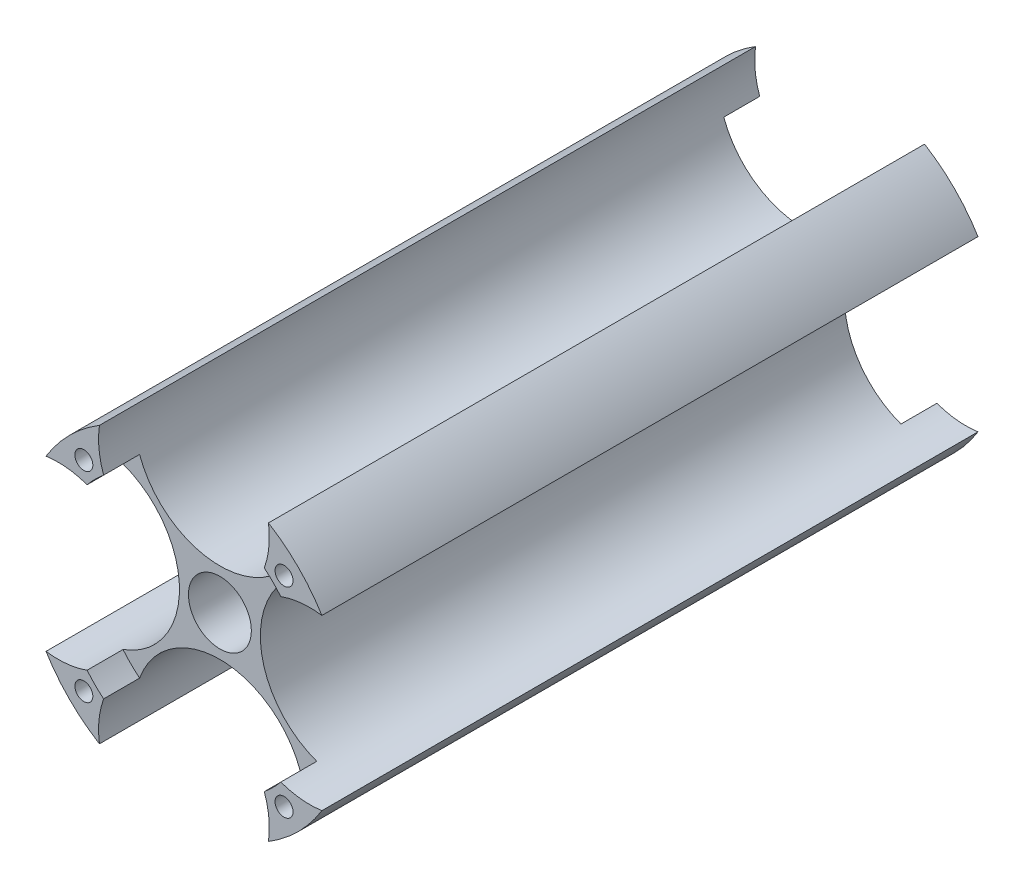
SolidWorks part; units mm, degrees
material "ABS"
ref_plane "Спереди" through (0, 0, 0) normal (0, 0, 1) x (1, 0, 0)
ref_plane "Сверху" through (0, 0, 0) normal (0, 1, 0) x (1, 0, 0)
ref_plane "Справа" through (0, 0, 0) normal (1, 0, 0) x (0, 0, -1)
sketch "Эскиз1" plane through (0, 0, 0) normal (0, 0, 1) x (1, 0, 0)
  line L0 (0, 0) -> (0, -18) construction
  line L1 (0, 0) -> (0, 18) construction
  line L2 (0, 0) -> (-18.5984, 18.5984) construction
  line L3 (0, 0) -> (-14, 0) construction
  circle A0 centre (0, 0) radius 18
  circle A1 centre (0, -14) radius 9.5
  circle A2 centre (-14, 0) radius 9.5
  circle A3 centre (0, 14) radius 9.5
  circle A7 centre (0, 0) radius 3.5
  circle A8 centre (14, 0) radius 9.5
  circle A9 centre (-11.1369, 11.1369) radius 1
  circle A10 centre (11.1369, 11.1369) radius 1
  circle A11 centre (11.1369, -11.1369) radius 1
  circle A12 centre (-11.1369, -11.1369) radius 1
  point P13 (0, 0)
  point P17 (11.5447, 10.6852)
  point P18 (0, 0)
  point P20 (0, 0)
  point P28 (0, 0)
  dimension "D1" = 19
  dimension "D4" = 36
  dimension "D5" = 45
  dimension "D7" = 7
  dimension "D6" = 2
  dimension "D2" = 14
  dimension "D8" = 15.75
  dimension "D3" = 4
  dimension "D9" = 4
extrude "Бобышка-Вытянуть1" add sketch "Эскиз1" along normal blind 65
sketch "Эскиз2" plane through (0, 0, 65) normal (0, 0, 1) x (1, 0, 0)
  circle A0 centre (0, 0) radius 14
  circle A1 centre (14, 0) radius 9.5
  circle A2 centre (14, 0) radius 9.5
  circle A3 centre (0, 14) radius 9.5
  circle A4 centre (0, 14) radius 9.5
  circle A5 centre (-14, 0) radius 9.5
  circle A6 centre (-14, 0) radius 9.5
  circle A7 centre (0, -14) radius 9.5
  circle A8 centre (0, -14) radius 9.5
  circle A9 centre (0, 0) radius 18
  circle A10 centre (0, 0) radius 18
  circle A11 centre (-11.1369, -11.1369) radius 1
  circle A12 centre (-11.1369, -11.1369) radius 1
  circle A13 centre (11.1369, -11.1369) radius 1
  circle A14 centre (11.1369, -11.1369) radius 1
  circle A15 centre (11.1369, 11.1369) radius 1
  circle A16 centre (11.1369, 11.1369) radius 1
  circle A17 centre (-11.1369, 11.1369) radius 1
  circle A18 centre (-11.1369, 11.1369) radius 1
  circle A19 centre (0, 0) radius 3.5
  circle A20 centre (0, 0) radius 3.5
  circle M11 centre (-11.1369, -11.1369) radius 1
  circle M12 centre (11.1369, -11.1369) radius 1
  circle M13 centre (11.1369, 11.1369) radius 1
  circle M14 centre (-11.1369, 11.1369) radius 1
  arc M15 (15.3482, -9.4038) -> (15.3482, 9.4038) centre (14, 0) cw
  arc M16 (15.3482, 9.4038) -> (9.4038, 15.3482) centre (0, 0) ccw
  arc M17 (9.4038, 15.3482) -> (-9.4038, 15.3482) centre (0, 14) cw
  arc M18 (-9.4038, 15.3482) -> (-15.3482, 9.4038) centre (0, 0) ccw
  arc M19 (-15.3482, 9.4038) -> (-15.3482, -9.4038) centre (-14, 0) cw
  arc M20 (-15.3482, -9.4038) -> (-9.4038, -15.3482) centre (0, 0) ccw
  arc M21 (-9.4038, -15.3482) -> (9.4038, -15.3482) centre (0, -14) cw
  arc M22 (9.4038, -15.3482) -> (15.3482, -9.4038) centre (0, 0) ccw
  dimension "D1" = 0
  dimension "D2" = 0
  dimension "D3" = 0
  dimension "D4" = 0
  dimension "D5" = 0
  dimension "D6" = 0
  dimension "D7" = 0
  dimension "D8" = 0
  dimension "D9" = 0
  dimension "D10" = 0
extrude "Бобышка-Вытянуть2" add sketch "Эскиз2" along normal blind 4 contours A0 M19 M20 M21 M11 | A0 M21 M22 M15 M12 | A0 M15 M16 M17 M13 | A0 M17 M18 M19 M14
sketch "Эскиз3" plane through (0, 0, 0) normal (0, 0, -1) x (-1, 0, 0)
  circle A1 centre (0, -14) radius 9.5
  circle A2 centre (0, -14) radius 9.5
  circle A3 centre (14, 0) radius 9.5
  circle A4 centre (14, 0) radius 9.5
  circle A5 centre (0, 14) radius 9.5
  circle A6 centre (0, 14) radius 9.5
  circle A7 centre (-14, 0) radius 9.5
  circle A8 centre (-14, 0) radius 9.5
  circle A9 centre (0, 0) radius 14
  circle A10 centre (0, 0) radius 14
  circle A11 centre (0, 0) radius 3.5
  circle A12 centre (0, 0) radius 3.5
  circle A13 centre (11.1369, 11.1369) radius 1
  circle A14 centre (11.1369, 11.1369) radius 1
  circle A15 centre (-11.1369, 11.1369) radius 1
  circle A16 centre (-11.1369, 11.1369) radius 1
  circle A17 centre (-11.1369, -11.1369) radius 1
  circle A18 centre (-11.1369, -11.1369) radius 1
  circle A19 centre (11.1369, -11.1369) radius 1
  circle A20 centre (11.1369, -11.1369) radius 1
  circle A21 centre (0, 0) radius 18
  circle A22 centre (0, 0) radius 18
  circle M12 centre (11.1369, -11.1369) radius 1
  circle M13 centre (-11.1369, -11.1369) radius 1
  circle M14 centre (-11.1369, 11.1369) radius 1
  circle M15 centre (11.1369, 11.1369) radius 1
  arc M16 (-15.3482, 9.4038) -> (-15.3482, -9.4038) centre (-14, 0) cw
  arc M17 (-15.3482, -9.4038) -> (-9.4038, -15.3482) centre (0, 0) ccw
  arc M18 (-9.4038, -15.3482) -> (9.4038, -15.3482) centre (0, -14) cw
  arc M19 (9.4038, -15.3482) -> (15.3482, -9.4038) centre (0, 0) ccw
  arc M20 (15.3482, -9.4038) -> (15.3482, 9.4038) centre (14, 0) cw
  arc M21 (15.3482, 9.4038) -> (9.4038, 15.3482) centre (0, 0) ccw
  arc M22 (9.4038, 15.3482) -> (-9.4038, 15.3482) centre (0, 14) cw
  arc M23 (-9.4038, 15.3482) -> (-15.3482, 9.4038) centre (0, 0) ccw
  dimension "D1" = 0
  dimension "D2" = 0
  dimension "D3" = 0
  dimension "D4" = 0
  dimension "D5" = 0
  dimension "D6" = 0
  dimension "D7" = 0
  dimension "D8" = 0
  dimension "D9" = 0
  dimension "D10" = 0
  dimension "D11" = 0
extrude "Бобышка-Вытянуть3" add sketch "Эскиз3" along normal blind 4 contours A10 M22 M23 M16 M14 | A10 M16 M17 M18 M13 | A10 M18 M19 M20 M12 | A10 M20 M21 M22 M15
